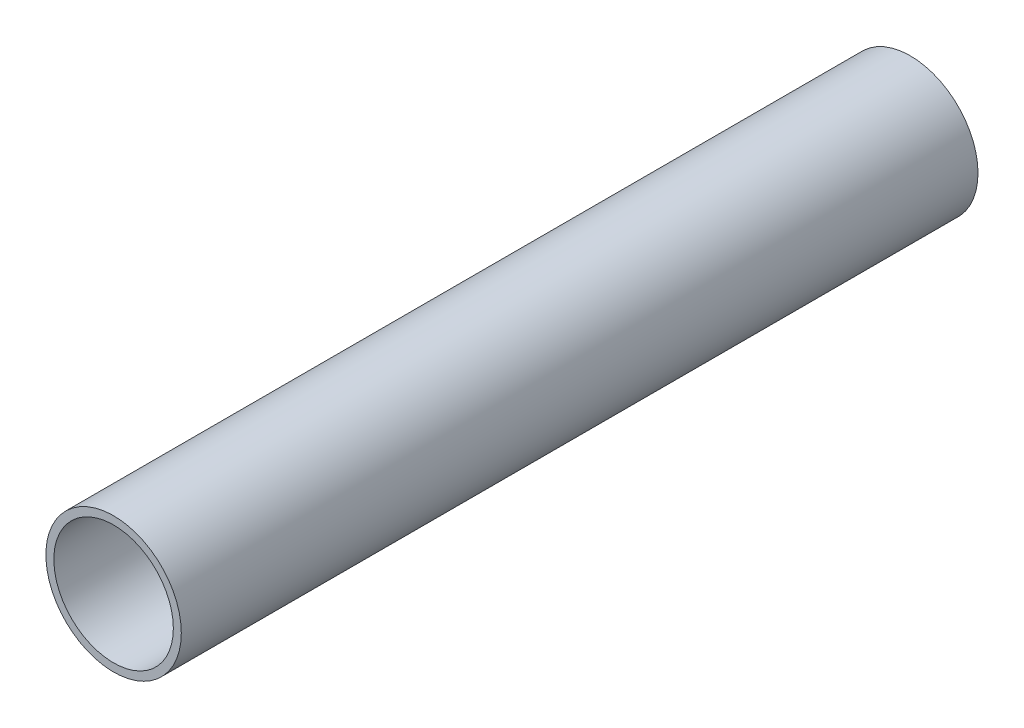
SolidWorks part; units mm, degrees
ref_plane "Front Plane" through (0, 0, 0) normal (0, 0, 1) x (1, 0, 0)
ref_plane "Top Plane" through (0, 0, 0) normal (0, 1, 0) x (1, 0, 0)
ref_plane "Right Plane" through (0, 0, 0) normal (1, 0, 0) x (0, 0, -1)
sketch "Sketch1" plane through (0, 0, 0) normal (0, 0, 1) x (1, 0, 0)
  circle A0 centre (0, 0) radius 15
  circle A1 centre (0, 0) radius 17
  dimension "D1" = 30
  dimension "D2" = 2
extrude "Boss-Extrude1" add sketch "Sketch1" along normal mid plane 200 contours A1 A0
